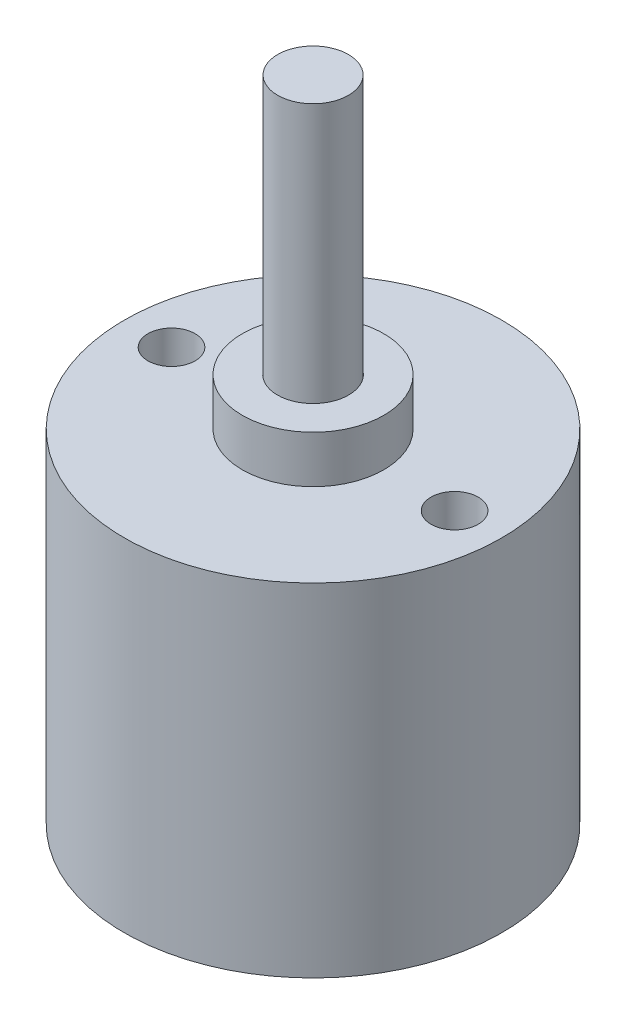
SolidWorks part; units mm, degrees
material "Acero inoxidable al cromo"
ref_plane "Alzado" through (0, 0, 0) normal (0, 0, 1) x (1, 0, 0)
ref_plane "Planta" through (0, 0, 0) normal (0, 1, 0) x (1, 0, 0)
ref_plane "Vista lateral" through (0, 0, 0) normal (1, 0, 0) x (0, 0, -1)
sketch "Croquis1" plane through (0, 0, 0) normal (0, 1, 0) x (1, 0, 0)
  circle A0 centre (0, 0) radius 8
extrude "Saliente-Extruir1" add sketch "Croquis1" along normal blind 14.5
sketch "Croquis2" plane through (0, 14.5, 0) normal (0, 1, 0) x (1, 0, 0)
  line L0 (8, 0) -> (7, 0) construction
  line L1 (-7, 0) -> (-5, 0) construction
  line L2 (-7, 0) -> (-8, 0) construction
  line L3 (-5, 0) -> (5, 0) construction
  line L4 (5, 0) -> (7, 0) construction
  circle A0 centre (0, 0) radius 8 construction
  circle A1 centre (6, 0) radius 1
  circle A2 centre (-6, 0) radius 1
  circle A3 centre (0, 0) radius 1.51
extrude "Cortar-Extruir1" cut sketch "Croquis2" against normal blind 5
sketch "Croquis3" plane through (0, 14.5, 0) normal (0, 1, 0) x (1, 0, 0)
  circle A0 centre (0, 0) radius 3
  circle A1 centre (0, 0) radius 1.51
extrude "Saliente-Extruir2" add sketch "Croquis3" along normal blind 2
sketch "Croquis4" plane through (0, 9.5, 0) normal (0, 1, 0) x (1, 0, 0)
  circle A0 centre (0, 0) radius 1.5
extrude "Saliente-Extruir3" add sketch "Croquis4" along normal blind 18
